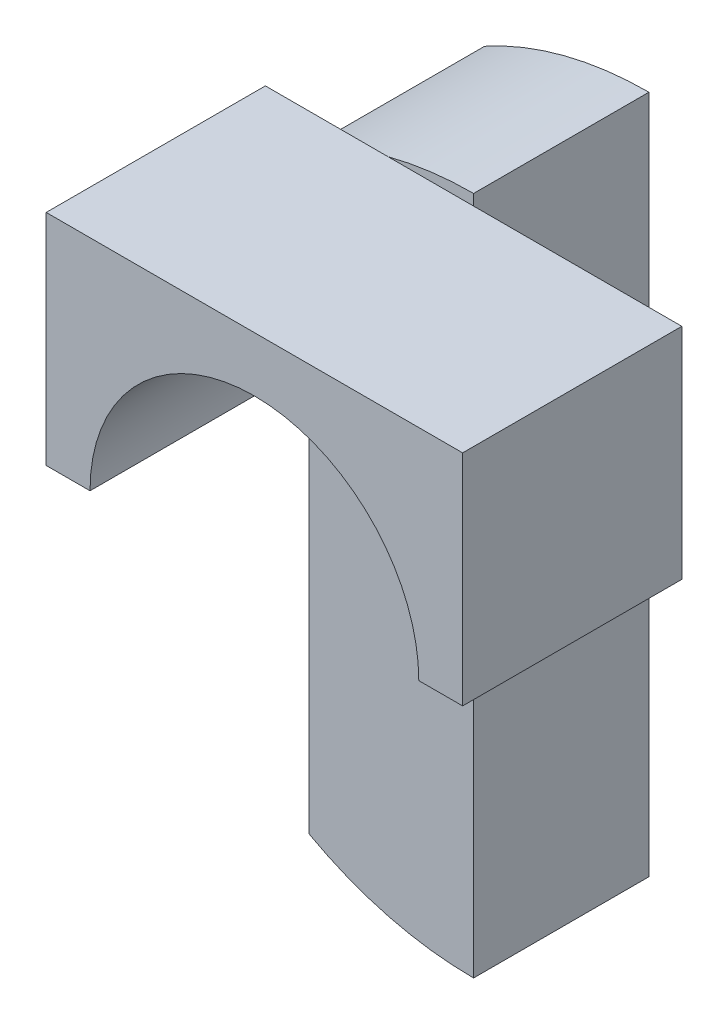
SolidWorks part; units mm, degrees
ref_plane "前视基准面" through (0, 0, 0) normal (0, 0, 1) x (1, 0, 0)
ref_plane "上视基准面" through (0, 0, 0) normal (0, 1, 0) x (1, 0, 0)
ref_plane "右视基准面" through (0, 0, 0) normal (1, 0, 0) x (0, 0, -1)
sketch "草图1" plane through (0, 0, 0) normal (0, 0, 1) x (1, 0, 0)
  line L1 (0, 15.5) -> (0, -15.5)
  line L2 (-7.5, 13.5647) -> (-7.5, -13.5647)
  arc A2 (0, 15.5) -> (-7.5, 13.5647) centre (0, 0) ccw
  arc A3 (-7.5, -13.5647) -> (0, -15.5) centre (0, 0) ccw
extrude "凸台-拉伸1" add sketch "草图1" along normal blind 8
sketch "草图2" plane through (0, 0, 8) normal (0, 0, 1) x (1, 0, 0)
  line L0 (-9.5, -5) -> (-9.5, 5) construction
  line L1 (7.5, 5) -> (-7.5, 5) construction
  line L2 (-7.5, 13.5647) -> (-7.5, -13.5647) construction
  line L3 (7.5, 5) -> (9.5, 5)
  line L4 (9.5, 5) -> (9.5, 15)
  line L5 (9.5, 15) -> (-9.5, 15)
  line L6 (-7.5, 5) -> (-9.5, 5)
  line L7 (-9.5, 5) -> (-9.5, 15)
  line L8 (9.5, -5) -> (9.5, 5) construction
  arc A0 (-7.5, 5) -> (7.5, 5) centre (0, 5) ccw construction
  arc A1 (7.5, 5) -> (-7.5, 5) centre (0, 5) ccw
  dimension "D1" = 10
extrude "凸台-拉伸2" add sketch "草图2" along normal blind 10
